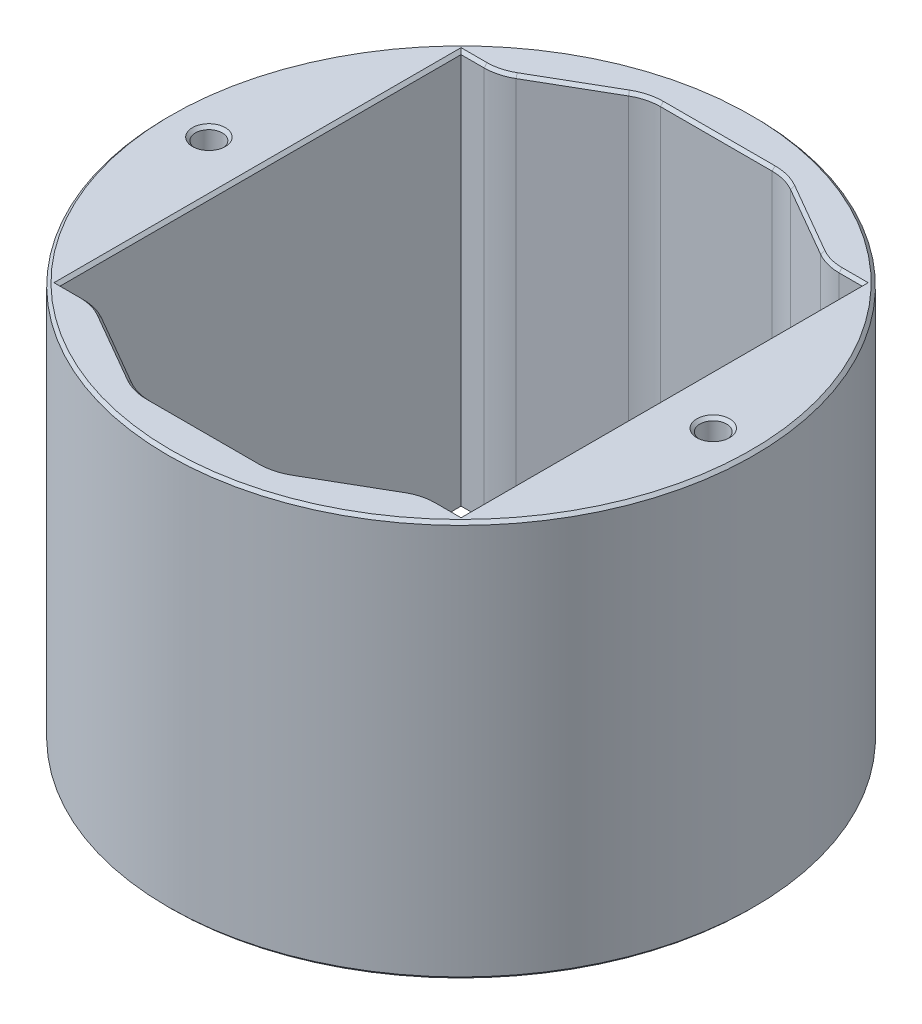
SolidWorks part; units mm, degrees
material "ABS"
ref_plane "Front Plane" through (0, 0, 0) normal (0, 0, 1) x (1, 0, 0)
ref_plane "Top Plane" through (0, 0, 0) normal (0, 1, 0) x (1, 0, 0)
ref_plane "Right Plane" through (0, 0, 0) normal (1, 0, 0) x (0, 0, -1)
sketch "Holder Section Profile" plane through (0, 0, 0) normal (0, 1, 0) x (1, 0, 0)
  circle A0 centre (0, 0) radius 73.787
  dimension "D1" = 147.574
extrude "Holder Section Body" add sketch "Holder Section Profile" along normal blind 100 contours A0
sketch "Payload Hole Profile" plane through (0, 100, 0) normal (0, 1, 0) x (1, 0, 0)
  line L1 (-50.5, -50.5) -> (50.5, -50.5)
  line L2 (-50.5, -50.5) -> (-50.5, 50.5)
  line L3 (-50.5, 50.5) -> (50.5, 50.5)
  line L4 (50.5, -50.5) -> (50.5, 50.5)
  line L5 (-50.5, -50.5) -> (50.5, 50.5) construction
  line L6 (-50.5, 50.5) -> (50.5, -50.5) construction
  point P0 (0, 0)
  dimension "D1" = 101
  dimension "D2" = 101
extrude "Payload Hole Cut" cut sketch "Payload Hole Profile" against normal through all
sketch "Access Hole Profile" plane through (0, 100, 0) normal (0, 1, 0) x (1, 0, 0)
  line L0 (-17.4625, -64.262) -> (17.4625, -64.262)
  line L1 (-50.5, -50.5) -> (50.5, -50.5) construction
  line L2 (-50.5, -50.5) -> (50.5, -50.5) construction
  line L3 (-17.4625, -64.262) -> (-41.299, -50.5)
  line L4 (17.4625, -64.262) -> (41.299, -50.5)
  line L5 (-41.299, -50.5) -> (41.299, -50.5)
  point P4 (0, -50.5)
  point P5 (0, -64.262)
  dimension "D1" = 34.925
  dimension "D2" = 30
  dimension "D3" = 30
  dimension "D4" = 13.762
extrude "Access Hole Cut" cut sketch "Access Hole Profile" against normal through all
ref_plane "Plane1" through (0, 0, 0) normal (0, 0, -1) x (-1, 0, 0)
mirror "Access Hole Mirror" about plane through (0, 0, 0) normal (0, 0, -1) of "Access Hole Cut"
fillet "Fillet1" radius 12.7 8 edges at (17.4625, 50, 64.262) (41.299, 50, 50.5) (-17.4625, 50, 64.262) (-41.299, 50, 50.5) (41.299, 50, -50.5) (17.4625, 50, -64.262) (-17.4625, 50, -64.262) (-41.299, 50, -50.5)
sketch "Threaded Rod Hole Profile" plane through (0, 100, 0) normal (0, 1, 0) x (1, 0, 0)
  line L0 (-63.5, 0) -> (63.5, 0) construction
  circle A0 centre (-63.5, 0) radius 3.3782
  circle A1 centre (63.5, 0) radius 3.3782
  point P4 (0, 0)
  dimension "D1" = 63.5
  dimension "D2" = 6.7564
extrude "Threaded Rod Hole Cut" cut sketch "Threaded Rod Hole Profile" against normal through all
chamfer "Chamfer1" distance 0.762 angle 45 46 edges at (17.3465, 0, 63.8293) (0, 0, 64.262) (-17.3465, 0, 63.8293) (-29.3807, 0, 57.381) (-41.4149, 0, 50.9327) (-47.601, 0, 50.5) (-50.5, 0, 0) (-47.601, 0, -50.5) (-41.4149, 0, -50.9327) (-29.3807, 0, -57.381) (-17.3465, 0, -63.8293) (0, 0, -64.262) (17.3465, 0, -63.8293) (29.3807, 0, -57.381) (41.4149, 0, -50.9327) (47.601, 0, -50.5) (50.5, 0, 0) (47.601, 0, 50.5) (41.4149, 0, 50.9327) (29.3807, 0, 57.381) (0, 0, 73.787) (63.5, 0, 3.3782) (-63.5, 0, 3.3782) (50.5, 100, 0) (47.601, 100, -50.5) (41.4149, 100, -50.9327) (29.3807, 100, -57.381) (17.3465, 100, -63.8293) (0, 100, -64.262) (-17.3465, 100, -63.8293) (-29.3807, 100, -57.381) (-41.4149, 100, -50.9327) (-47.601, 100, -50.5) (-50.5, 100, 0) (-47.601, 100, 50.5) (-41.4149, 100, 50.9327) (-29.3807, 100, 57.381) (-17.3465, 100, 63.8293) (0, 100, 64.262) (17.3465, 100, 63.8293) (29.3807, 100, 57.381) (41.4149, 100, 50.9327) (47.601, 100, 50.5) (0, 100, 73.787) (63.5, 100, 3.3782) (-63.5, 100, 3.3782)
